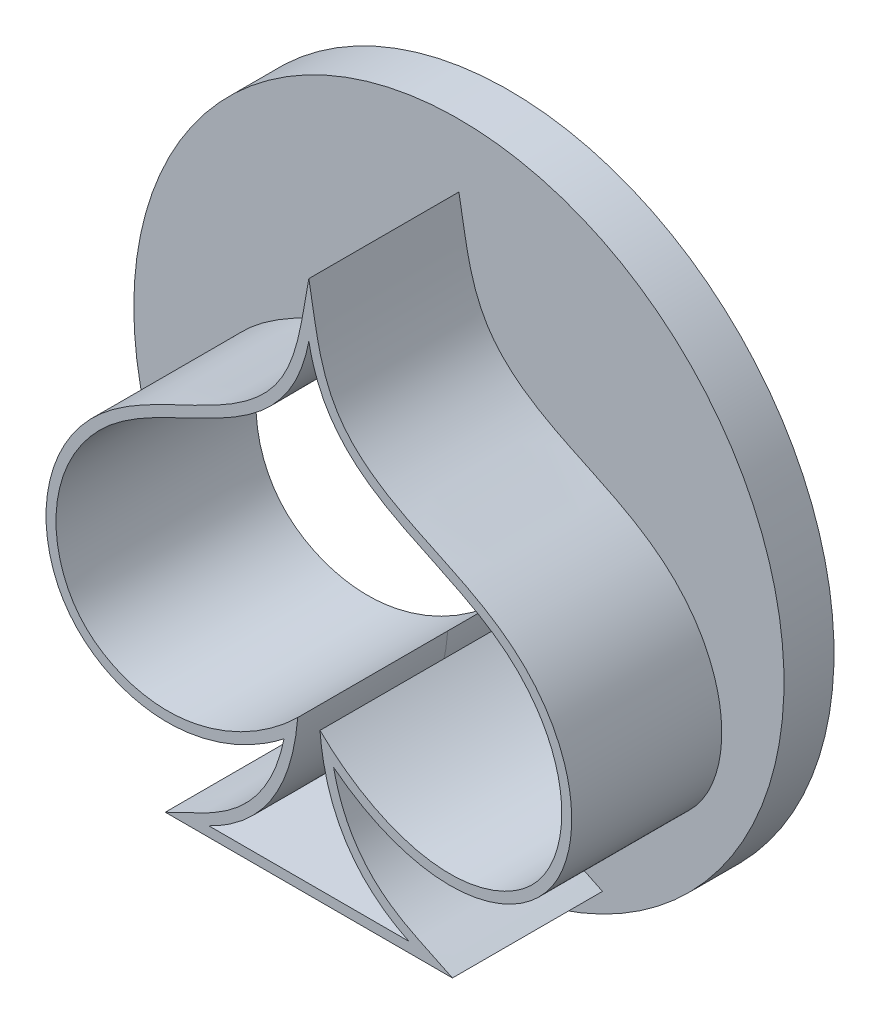
SolidWorks part; units mm, degrees
ref_plane "Front Plane" through (0, 0, 0) normal (0, 0, 1) x (1, 0, 0)
ref_plane "Top Plane" through (0, 0, 0) normal (0, 1, 0) x (1, 0, 0)
ref_plane "Right Plane" through (0, 0, 0) normal (1, 0, 0) x (0, 0, -1)
sketch "Sketch2" plane through (0, 0, 0) normal (0, 0, 1) x (1, 0, 0)
  line L0 (0, 0) -> (0, 9.3905) construction
  line L1 (2, 0) -> (-2, 0)
  line L2 (2.8707, -0.2) -> (-2.8707, -0.2)
  spline S0 degree 2 poles (-2, 0) (-0.3838, 0.7838) (-0.2227, 2.7636) knots 0 0 0 1 1 1
  spline S1 degree 3 poles (-0.2227, 2.7636) (-0.9806, 2.0167) (-2.6325, 1.1707) (-4.5967, 2.1021) (-5.1594, 3.4259) (-4.9658, 4.8005) (-3.2733, 7.0981) (-0.4349, 7.0737) (0, 9.3905) knots 0 0 0 0 0.233244 0.336386 0.419961 0.519898 0.616444 1 1 1 1
  spline S2 degree 2 poles (2, 0) (0.3838, 0.7838) (0.2227, 2.7636) knots 0 0 0 1 1 1
  spline S3 degree 3 poles (0.2227, 2.7636) (0.9806, 2.0167) (2.6325, 1.1707) (4.5967, 2.1021) (5.1594, 3.4259) (4.9658, 4.8005) (3.2733, 7.0981) (0.4349, 7.0737) (0, 9.3905) knots 0 0 0 0 0.233244 0.336386 0.419961 0.519898 0.616444 1 1 1 1
  spline S4 degree 1 poles (-0.495, 2.2595) (0, 10.4747) knots 0 0 1 1 construction
  spline S5 degree 1 poles (0.495, 2.2595) (0, 10.4747) knots 0 0 1 1 construction
  spline S6 degree 1 poles (2.8707, -0.2) (0.495, 2.2595) knots 0 0 1 1 construction
  spline S7 degree 1 poles (-2.8707, -0.2) (-0.495, 2.2595) knots 0 0 1 1 construction
  spline S8 degree 3 poles (-0.495, 2.2595) (-0.9988, 1.8669) (-1.8865, 1.4082) (-3.1994, 1.341) (-4.1796, 1.6536) (-4.9456, 2.3556) (-5.4019, 3.6543) (-5.0963, 4.9997) (-4.268, 6.0185) (-3.4876, 6.5612) (-2.6506, 6.9674) (-1.8298, 7.3495) (-1.105, 7.8002) (-0.5331, 8.4011) (-0.1889, 9.2633) (-0.0718, 10.092) (0, 10.4747) knots 0.037621 0.037621 0.037621 0.037621 0.165142 0.228903 0.292664 0.356424 0.420185 0.547706 0.611467 0.675227 0.738988 0.802749 0.866509 0.93027 0.994031 1.057791 1.057791 1.057791 1.057791
  spline S9 degree 3 poles (0, 10.4747) (0.0718, 10.092) (0.1889, 9.2633) (0.5331, 8.4011) (1.105, 7.8002) (1.8298, 7.3495) (2.6506, 6.9674) (3.4876, 6.5612) (4.268, 6.0185) (5.0963, 4.9997) (5.4019, 3.6543) (4.9456, 2.3556) (4.1796, 1.6536) (3.1994, 1.341) (1.8865, 1.4082) (0.9988, 1.8669) (0.495, 2.2595) knots 0.037621 0.037621 0.037621 0.037621 0.101382 0.165142 0.228903 0.292664 0.356424 0.420185 0.483946 0.547706 0.675227 0.738988 0.802749 0.866509 0.93027 1.057791 1.057791 1.057791 1.057791
  spline S10 degree 2 poles (0.495, 2.2595) (0.6407, 1.5541) (1.2598, 0.7149) (1.8707, 0.2781) (2.5382, -0.0364) (2.8707, -0.2) knots -0.242381 -0.242381 -0.242381 0.169631 0.444306 0.650312 0.856317 0.856317 0.856317
  spline S11 degree 2 poles (-2.8707, -0.2) (-2.5382, -0.0364) (-1.8707, 0.2781) (-1.2598, 0.7149) (-0.6407, 1.5541) (-0.495, 2.2595) knots -0.242381 -0.242381 -0.242381 -0.036375 0.169631 0.444306 0.856317 0.856317 0.856317
  dimension "D1" = 0.2
  dimension "D2" = 2
extrude "Boss-Extrude1" add sketch "Sketch2" along normal blind 3
sketch "Sketch3" plane through (0, 0, 0) normal (0, 0, -1) x (-1, 0, 0)
  line L0 (0, 10.4747) -> (0, 0) construction
  circle A0 centre (0, 5.2373) radius 6.5
extrude "Boss-Extrude2" add sketch "Sketch3" along normal blind 1
sketch "Sketch4" plane through (0, 0, 0) normal (0, 0, 1) x (1, 0, 0)
  line L0 (-2, 0) -> (2, 0) construction
  line L1 (-2, 0) -> (2, 0)
  parabola Q0 (2, 0) -> (0.2227, 2.7636) focus (2.0347, 1.7126) apex (0.9426, 0.815) construction
  parabola Q1 (-0.2227, 2.7636) -> (-2, 0) focus (-2.0347, 1.7126) apex (-0.9426, 0.815) construction
  parabola Q2 (2, 0) -> (0.2227, 2.7636) focus (2.0347, 1.7126) apex (0.9426, 0.815)
  parabola Q3 (-0.2227, 2.7636) -> (-2, 0) focus (-2.0347, 1.7126) apex (-0.9426, 0.815)
  spline S0 degree 3 poles (1328.868, -1490.9814) (-38.0813, 165.7081) (-12.5065, -6.0083) (4.5967, 2.1021) (5.1594, 3.4259) (4.9658, 4.8005) (-4.5404, 17.7057) (-75.9518, -53.1253) (1194.8472, 1613.0391) knots -3.236789 -3.236789 -3.236789 -3.236789 0.233244 0.336386 0.419961 0.519898 0.616444 3.677847 3.677847 3.677847 3.677847 only from (0.2227, 2.7636) to (0, 9.3905) construction
  spline S1 degree 3 poles (-1194.8223, 1613.0065) (75.9509, -53.1244) (4.5404, 17.7056) (-4.9658, 4.8005) (-5.1594, 3.4259) (-4.5967, 2.1021) (12.5065, -6.0083) (38.0812, 165.7072) (-1328.8564, -1490.9673) knots -2.677827 -2.677827 -2.677827 -2.677827 0.383556 0.480102 0.580039 0.663614 0.766756 4.23678 4.23678 4.23678 4.23678 only from (0, 9.3905) to (-0.2227, 2.7636) construction
  spline S2 degree 3 poles (0.2227, 2.7636) (0.9806, 2.0167) (2.6325, 1.1707) (4.5967, 2.1021) (5.1594, 3.4259) (4.9658, 4.8005) (3.2733, 7.0981) (0.4349, 7.0737) (0, 9.3905) knots 0 0 0 0 0.233244 0.336386 0.419961 0.519898 0.616444 1 1 1 1
  spline S3 degree 3 poles (0, 9.3905) (-0.4349, 7.0737) (-3.2733, 7.0981) (-4.9658, 4.8005) (-5.1594, 3.4259) (-4.5967, 2.1021) (-2.6325, 1.1707) (-0.9806, 2.0167) (-0.2227, 2.7636) knots 0 0 0 0 0.383556 0.480102 0.580039 0.663614 0.766756 1 1 1 1
extrude "Cut-Extrude1" cut sketch "Sketch4" against normal blind 1
